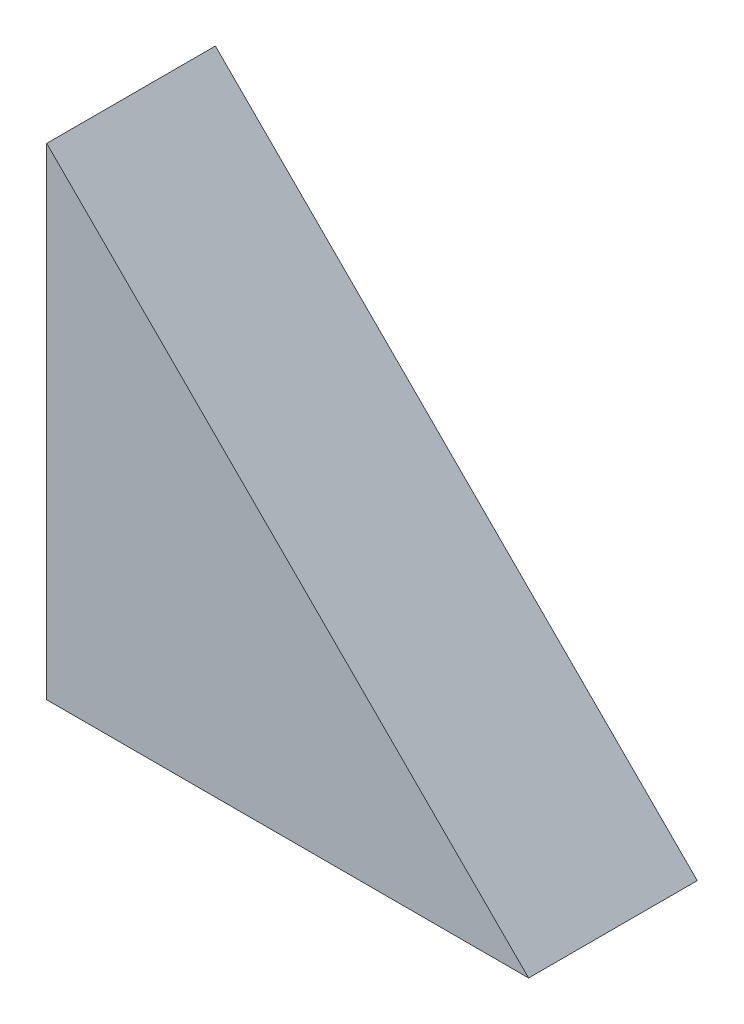
SolidWorks part; units mm, degrees
ref_plane "Front Plane" through (0, 0, 0) normal (0, 0, 1) x (1, 0, 0)
ref_plane "Top Plane" through (0, 0, 0) normal (0, 1, 0) x (1, 0, 0)
ref_plane "Right Plane" through (0, 0, 0) normal (1, 0, 0) x (0, 0, -1)
sketch "Sketch1" plane through (0, 0, 0) normal (0, 0, 1) x (1, 0, 0)
  line L0 (0, 0) -> (0, -10)
  line L1 (0, -10) -> (10, -10)
  line L2 (10, -10) -> (0, 0)
  dimension "D1" = 10
extrude "Boss-Extrude1" add sketch "Sketch1" along normal blind 3.5
